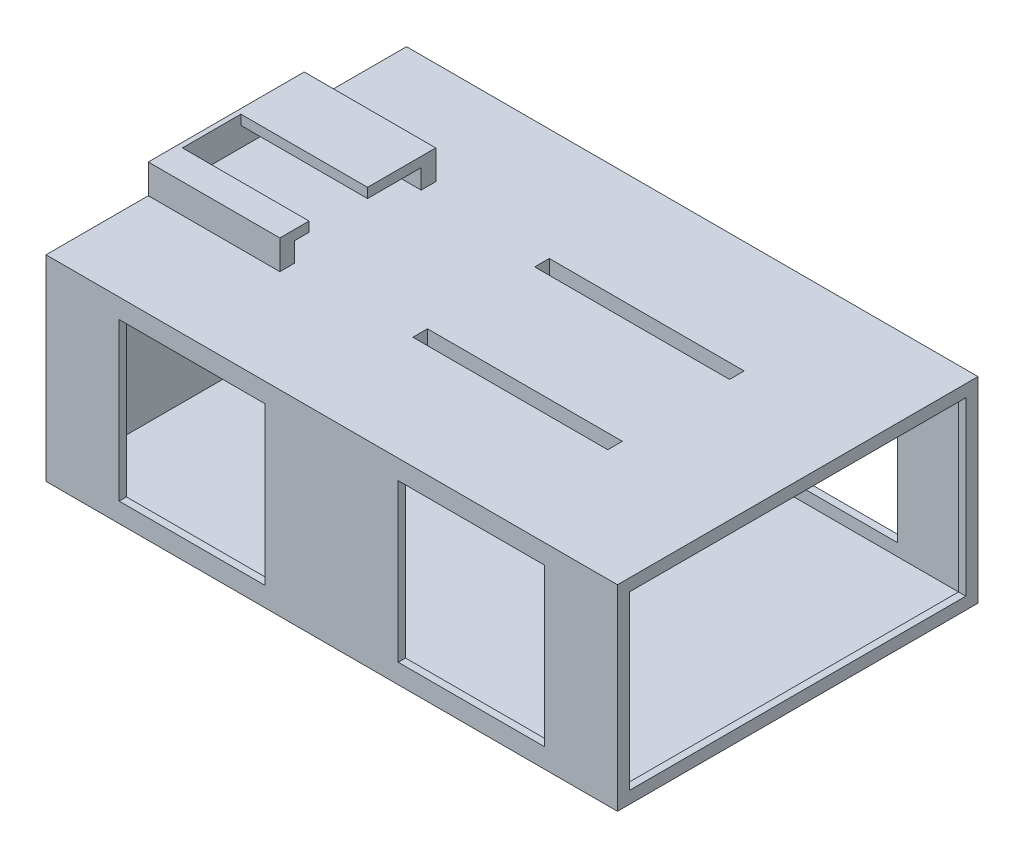
SolidWorks part; units mm, degrees
ref_plane "Front Plane" through (0, 0, 0) normal (0, 0, 1) x (1, 0, 0)
ref_plane "Top Plane" through (0, 0, 0) normal (0, 1, 0) x (1, 0, 0)
ref_plane "Right Plane" through (0, 0, 0) normal (1, 0, 0) x (0, 0, -1)
sketch "Sketch1" plane through (0, 0, 0) normal (0, 1, 0) x (1, 0, 0)
  line L0 (1.5, 1.5) -> (1.5, 72.5)
  line L1 (0, 0) -> (117.3, 0)
  line L2 (0, 0) -> (0, 74)
  line L3 (0, 74) -> (117.3, 74)
  line L4 (117.3, 0) -> (117.3, 74)
  line L5 (1.5, 72.5) -> (115.8, 72.5)
  line L6 (115.8, 1.5) -> (115.8, 72.5)
  line L7 (1.5, 1.5) -> (115.8, 1.5)
  dimension "D1" = 117.3
  dimension "D2" = 74
  dimension "D3" = 1.5
extrude "Boss-Extrude1" add sketch "Sketch1" along normal blind 40.28 contours L7 L6 L5 L0 | L3 L4 L1 L2
ref_plane "Plane1" through (0, 0, 0) normal (1, 0, 0) x (0, 0, -1)
sketch "Sketch5" plane through (0, 0, 0) normal (0, -1, 0) x (1, 0, 0)
  line L1 (0, 0) -> (117.3, 0)
  line L2 (0, 0) -> (0, -74)
  line L3 (0, -74) -> (117.3, -74)
  line L4 (117.3, 0) -> (117.3, -74)
extrude "Boss-Extrude3" add sketch "Sketch5" against normal blind 1.5
sketch "Sketch7" plane through (117.3, 0, 0) normal (1, 0, 0) x (0, 0, -1)
  line L16 (2.5, 2.5) -> (71.5, 2.5)
  line L17 (71.5, 2.5) -> (71.5, 37.78)
  line L18 (71.5, 37.78) -> (2.5, 37.78)
  line L19 (2.5, 37.78) -> (2.5, 2.5)
  line L20 (2.5, 2.5) -> (71.5, 2.5)
  line L21 (71.5, 2.5) -> (71.5, 37.78)
  line L22 (71.5, 37.78) -> (2.5, 37.78)
  line L23 (2.5, 37.78) -> (2.5, 2.5)
  dimension "D1" = 2.5
extrude "Cut-Extrude3" cut sketch "Sketch7" against normal blind 2 contours L22 L23 L20 L21
sketch "Sketch8" plane through (0, 40.28, 0) normal (0, 1, 0) x (1, 0, 0)
  line L1 (0, 74) -> (117.3, 74)
  line L2 (0, 74) -> (0, 0)
  line L3 (0, 0) -> (117.3, 0)
  line L4 (117.3, 74) -> (117.3, 0)
extrude "Boss-Extrude4" add sketch "Sketch8" against normal blind 1.5
sketch "Sketch9" plane through (0, 40.28, 0) normal (0, 1, 0) x (1, 0, 0)
  line L0 (0, 37) -> (117.3, 37) construction
  line L1 (0, 0) -> (0, 74) construction
  line L2 (117.3, 0) -> (117.3, 74) construction
  line L6 (1, 53) -> (27, 53)
  line L7 (1, 24) -> (27, 24)
  line L8 (1, 24) -> (1, 21)
  line L9 (1, 21) -> (27, 21)
  line L10 (27, 24) -> (27, 21)
  line L11 (1, 24) -> (27, 21) construction
  line L12 (1, 21) -> (27, 24) construction
  line L13 (27, 50) -> (27, 53)
  line L14 (1, 50) -> (27, 50)
  line L15 (1, 50) -> (1, 53)
  point P12 (14, 22.5)
  dimension "D1" = 26
  dimension "D2" = 3
  dimension "D3" = 13
  dimension "D4" = 1
extrude "Boss-Extrude5" add sketch "Sketch9" along normal blind 6
sketch "Sketch10" plane through (0, 0, -50) normal (0, 0, 1) x (1, 0, 0)
  line L1 (1, 46.28) -> (27, 46.28)
  line L2 (1, 46.28) -> (1, 44.28)
  line L3 (1, 44.28) -> (27, 44.28)
  line L4 (27, 46.28) -> (27, 44.28)
  dimension "D1" = 2
extrude "Boss-Extrude6" add sketch "Sketch10" along normal blind 11
sketch "Sketch11" plane through (0, 0, -24) normal (0, 0, -1) x (-1, 0, 0)
  line L1 (-27, 46.28) -> (-1, 46.28)
  line L2 (-27, 46.28) -> (-27, 44.28)
  line L3 (-27, 44.28) -> (-1, 44.28)
  line L4 (-1, 46.28) -> (-1, 44.28)
  dimension "D1" = 2
extrude "Boss-Extrude7" add sketch "Sketch11" along normal blind 3
sketch "Sketch12" plane through (1, 0, 0) normal (-1, 0, 0) x (0, 0, 1)
  line L1 (-53, 46.28) -> (-21, 46.28)
  line L2 (-53, 46.28) -> (-53, 40.28)
  line L3 (-53, 40.28) -> (-21, 40.28)
  line L4 (-21, 46.28) -> (-21, 40.28)
extrude "Boss-Extrude8" add sketch "Sketch12" along normal blind 1
sketch "Sketch19" plane through (0, 0, 0) normal (0, 0, 1) x (1, 0, 0)
  line L0 (0, 40.28) -> (0, 0) construction
  line L1 (15, 36.28) -> (45, 36.28)
  line L2 (15, 36.28) -> (15, 4)
  line L3 (15, 4) -> (45, 4)
  line L4 (45, 36.28) -> (45, 4)
  line L5 (0, 0) -> (117.3, 0) construction
  line L6 (0, 40.28) -> (117.3, 40.28) construction
  line L7 (58.65, 40.28) -> (58.65, 0) construction
  line L9 (102.3, 4) -> (72.3, 4)
  line L10 (72.3, 36.28) -> (72.3, 4)
  line L11 (102.3, 36.28) -> (72.3, 36.28)
  line L12 (102.3, 36.28) -> (102.3, 4)
  dimension "D1" = 30
  dimension "D2" = 15
  dimension "D3" = 4
  dimension "D4" = 4
extrude "Cut-Extrude6" cut sketch "Sketch19" against normal through all
sketch "Sketch20" plane through (0, 38.78, 0) normal (0, -1, 0) x (1, 0, 0)
  line L0 (117.3, 0) -> (117.3, -74) construction
  line L5 (0, -37) -> (117.3, -37) construction
  line L6 (0, 0) -> (0, -74) construction
  line L8 (47.3, -19.5) -> (102.3, -19.5)
  line L9 (47.3, -19.5) -> (47.3, -54.5)
  line L10 (47.3, -54.5) -> (102.3, -54.5)
  line L11 (102.3, -19.5) -> (102.3, -54.5)
  line L12 (47.3, -19.5) -> (102.3, -54.5) construction
  line L13 (47.3, -54.5) -> (102.3, -19.5) construction
  point P0 (74.8, -37)
  dimension "D1" = 15
  dimension "D2" = 55
  dimension "D3" = 35
extrude "Boss-Extrude10" add sketch "Sketch20" along normal blind 13.5
sketch "Sketch22" plane through (0, 25.28, 0) normal (0, -1, 0) x (1, 0, 0)
  line L0 (47.3, -37) -> (102.3, -37) construction
  line L1 (52.3, -23) -> (92.3, -23)
  line L2 (52.3, -23) -> (52.3, -26)
  line L3 (52.3, -26) -> (92.3, -26)
  line L4 (92.3, -23) -> (92.3, -26)
  line L5 (47.3, -19.5) -> (47.3, -54.5) construction
  line L6 (102.3, -54.5) -> (102.3, -19.5) construction
  line L8 (52.3, -48) -> (92.3, -48)
  line L9 (92.3, -51) -> (92.3, -48)
  line L10 (52.3, -51) -> (92.3, -51)
  line L11 (52.3, -51) -> (52.3, -48)
  dimension "D1" = 3
  dimension "D2" = 40
  dimension "D3" = 14
  dimension "D4" = 5
extrude "Cut-Extrude7" cut sketch "Sketch22" against normal through all
